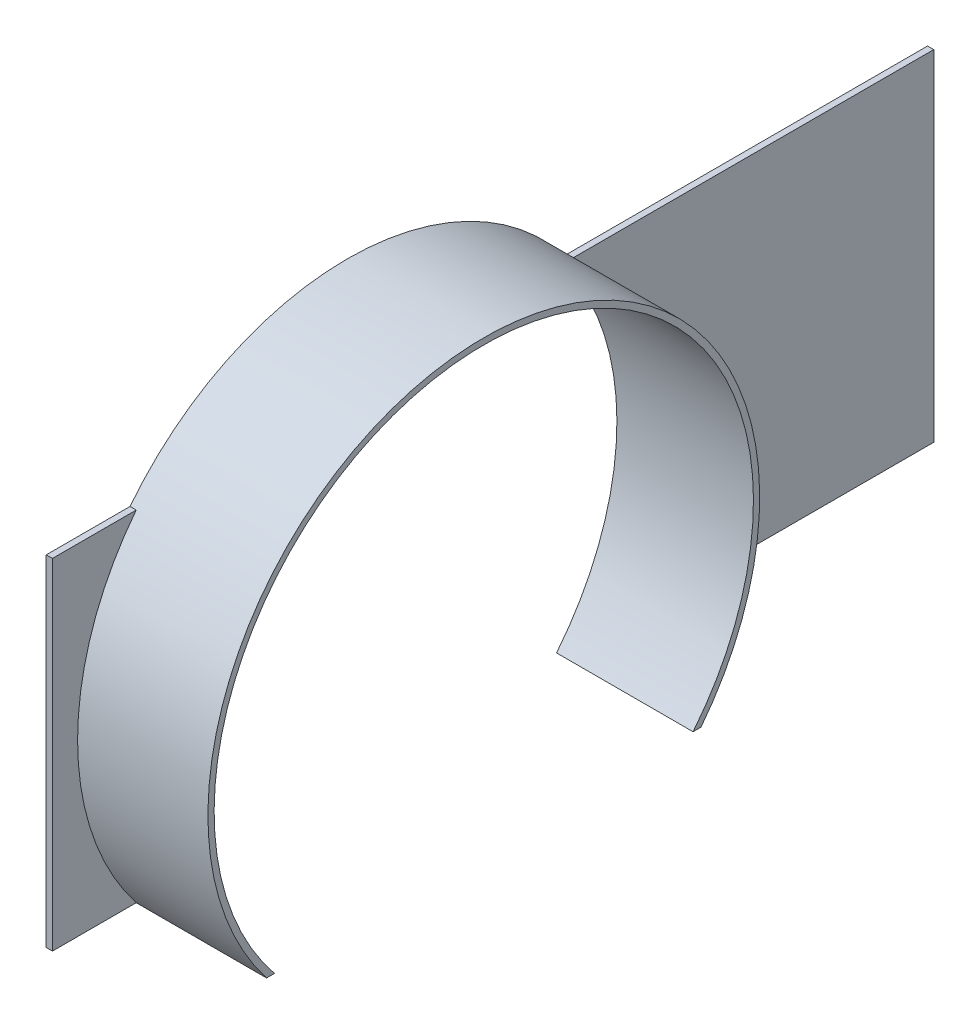
SolidWorks part; units mm, degrees
ref_plane "Front Plane" through (0, 0, 0) normal (0, 0, 1) x (1, 0, 0)
ref_plane "Top Plane" through (0, 0, 0) normal (0, 1, 0) x (1, 0, 0)
ref_plane "Right Plane" through (0, 0, 0) normal (1, 0, 0) x (0, 0, -1)
sketch "Sketch1" plane through (0, 0, 0) normal (-1, 0, 0) x (0, 0, 1)
  line L0 (-50, 109.6) -> (-50, 0) construction
  line L1 (-50, 0) -> (100, 0) construction
  line L2 (-45.0012, 0) -> (-42.4431, 0)
  line L3 (92.4431, 0) -> (95.0012, 0)
  arc A0 (-42.4431, 0) -> (92.4431, 0) centre (25, 54.8) cw
  arc A1 (-45.0012, 0) -> (95.0012, 0) centre (25, 54.8) cw
  dimension "D1" = 88.9
  dimension "D2" = 2
extrude "Boss-Extrude1" add sketch "Sketch1" against normal blind 42
sketch "Sketch2" plane through (0, 0, 0) normal (-1, 0, 0) x (0, 0, 1)
  line L0 (-50, 0) -> (100, 0) construction
  line L1 (-42.4431, 0) -> (-45.0012, 0)
  line L2 (92.4431, 0) -> (95.0012, 0)
  line L3 (95.0012, 0) -> (120, 0)
  line L4 (95.0012, 109.9319) -> (95.0012, 109.6)
  line L5 (95.0012, 109.6) -> (120, 109.6)
  line L6 (120, 109.6) -> (122, 109.6)
  line L8 (122, 109.6) -> (122, 0)
  line L10 (122, 0) -> (120, 0)
  line L11 (-45.0012, 0) -> (-160, 0)
  line L12 (-160, 0) -> (-162, 0)
  line L14 (-162, 0) -> (-162, 109.6)
  line L16 (-162, 109.6) -> (-160, 109.6)
  line L17 (-160, 109.6) -> (-45.0012, 109.6)
  arc A0 (-42.4431, 0) -> (92.4431, 0) centre (25, 54.8) cw
  arc A1 (92.4431, 0) -> (-42.4431, 0) centre (25, 54.8) ccw construction
  arc A2 (-45.0012, 0) -> (95.0012, 0) centre (25, 54.8) cw
  dimension "D2" = 2
  dimension "D1" = 2
  dimension "D3" = 109.6
  dimension "D4" = 114.9988
  dimension "D5" = 24.9988
extrude "Boss-Extrude2" add sketch "Sketch2" along normal blind 2 contours L11 A2 L17 L16 L14 L12 | A2 L1 A0 L2 | L5 A2 L3 L10 L8 L6
equation "\"gap\"= 1mm"
equation "\"casewidth\"= 2mm"
equation "\"D2@Sketch1\"=\"casewidth\""
equation "\"D1@Sketch2\"=\"casewidth\""
equation "\"D2@Sketch2\"=\"casewidth\""
equation "\"D1@Boss-Extrude2\"=\"casewidth\""
